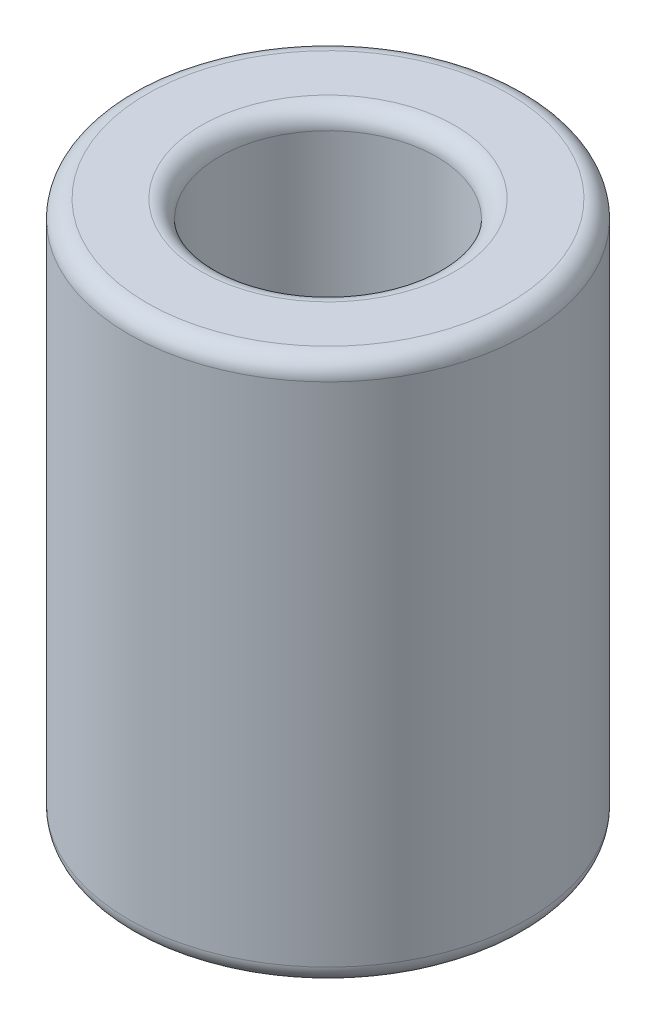
SolidWorks part; units mm, degrees
ref_plane "Front Plane" through (0, 0, 0) normal (0, 0, 1) x (1, 0, 0)
ref_plane "Top Plane" through (0, 0, 0) normal (0, 1, 0) x (1, 0, 0)
ref_plane "Right Plane" through (0, 0, 0) normal (1, 0, 0) x (0, 0, -1)
sketch "Sketch1" plane through (0, 0, 0) normal (0, 1, 0) x (1, 0, 0)
  circle A0 centre (0, 0) radius 11
  dimension "D1" = 22
extrude "Boss-Extrude1" add sketch "Sketch1" along normal blind 30
sketch "Sketch2" plane through (0, 30, 0) normal (0, 1, 0) x (1, 0, 0)
  circle A0 centre (0, 0) radius 6
  circle A1 centre (0, 0) radius 11 construction
  dimension "D1" = 5
extrude "Cut-Extrude1" cut sketch "Sketch2" against normal through all
fillet "Fillet2" radius 1 4 edges at (0, 0, 6) (0, 0, 11) (0, 30, 6) (0, 30, 11)
